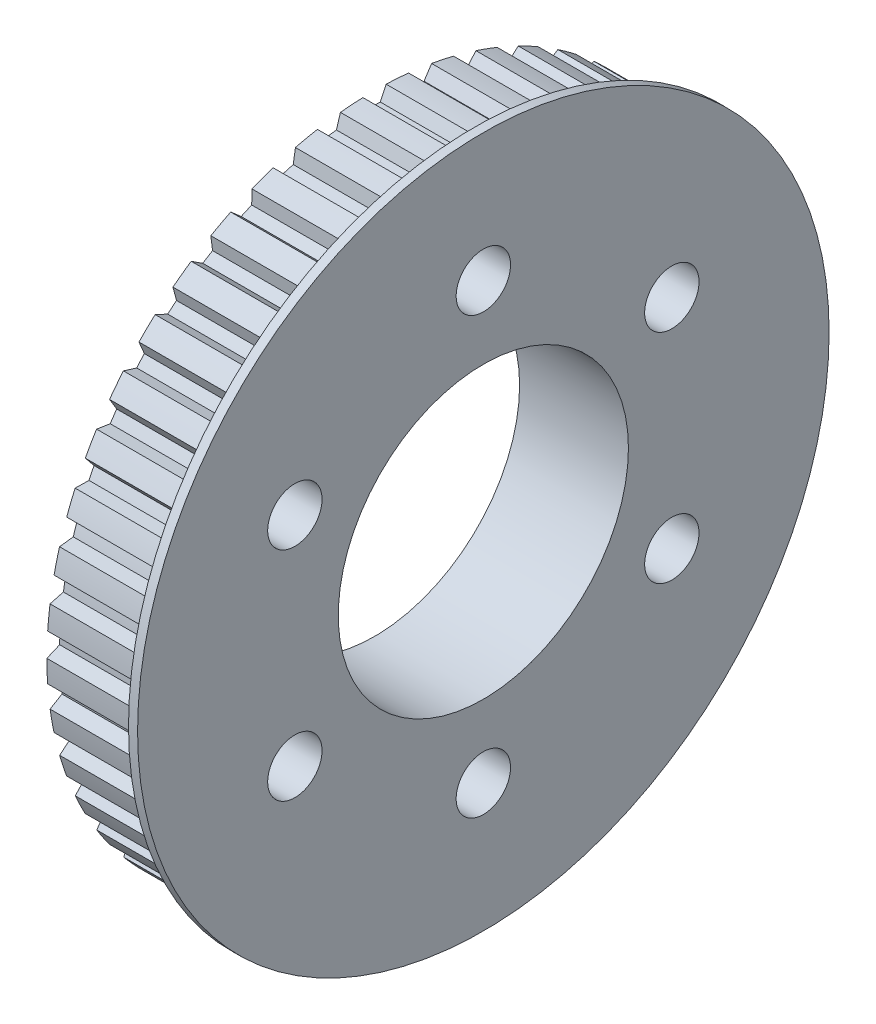
SolidWorks part; units mm, degrees
ref_plane "Front Plane" through (0, 0, 0) normal (0, 0, 1) x (1, 0, 0)
ref_plane "Top Plane" through (0, 0, 0) normal (0, 1, 0) x (1, 0, 0)
ref_plane "Right Plane" through (0, 0, 0) normal (1, 0, 0) x (0, 0, -1)
sketch "Sketch1" plane through (0, 0, 0) normal (1, 0, 0) x (0, 0, -1)
  line L0 (0, 36.13) -> (0, 0) construction
  circle A0 centre (0, 0) radius 36.13
  circle A1 centre (0, 0) radius 16
  point P19 (0, 0)
  dimension "D1" = 72.26
  dimension "D2" = 32
extrude "Boss-Extrude1" add sketch "Sketch1" along normal blind 11
sketch "Sketch2" plane through (0, 0, 0) normal (-1, 0, 0) x (0, 0, 1)
  line L0 (0, 0) -> (0, 36.13) construction
  line L1 (1.2799, 36.1073) -> (0.635, 34.7242)
  line L2 (-1.2799, 36.1073) -> (-0.635, 34.7242)
  line L3 (6.2926, 35.5778) -> (5.4615, 34.2979)
  line L4 (3.7577, 35.9341) -> (4.2039, 34.4746)
  line L5 (11.1829, 34.3558) -> (10.1817, 33.204)
  line L6 (8.7222, 35.0614) -> (8.9609, 33.5541)
  line L7 (15.8554, 32.4651) -> (14.7037, 31.4639)
  line L8 (13.5169, 33.5063) -> (13.5435, 31.9804)
  line L9 (20.2194, 29.9425) -> (18.9395, 29.1113)
  line L10 (18.0485, 31.299) -> (17.8625, 29.7843)
  line L11 (24.1898, 26.8371) -> (22.8067, 26.1921)
  line L12 (22.2289, 28.4825) -> (21.8339, 27.0084)
  line L13 (27.6894, 23.2093) -> (26.23, 22.7632)
  line L14 (25.9765, 25.1117) -> (25.3802, 23.7069)
  line L15 (30.6501, 19.1299) -> (29.1427, 18.8911)
  line L16 (29.2186, 21.2521) -> (28.4326, 19.9439)
  line L17 (33.0141, 14.678) -> (31.4882, 14.6514)
  line L18 (31.892, 16.9788) -> (30.9315, 15.7928)
  line L19 (34.7356, 9.9405) -> (33.2209, 10.1265)
  line L20 (33.9446, 12.3751) -> (32.8285, 11.3343)
  line L21 (35.781, 5.0095) -> (34.3069, 5.4045)
  line L22 (35.3365, 7.5305) -> (34.0864, 6.6551)
  line L23 (36.13, -0.019) -> (34.7252, 0.5773)
  line L24 (36.0407, 2.5393) -> (34.6809, 1.8464)
  line L25 (35.7757, -5.0472) -> (34.4676, -4.2612)
  line L26 (36.0433, -2.5013) -> (34.6003, -2.9982)
  line L27 (34.7251, -9.9771) -> (33.5391, -9.0166)
  line L28 (35.3444, -7.4932) -> (33.8463, -7.7844)
  line L29 (32.9987, -14.7128) -> (31.9579, -13.5966)
  line L30 (33.9576, -12.3393) -> (32.4336, -12.4192)
  line L31 (30.6299, -19.1621) -> (29.7546, -17.912)
  line L32 (31.9098, -16.9452) -> (30.3895, -16.8122)
  line L33 (27.665, -23.2385) -> (26.9721, -21.8787)
  line L34 (29.241, -21.2213) -> (27.754, -20.878)
  line L35 (24.1616, -26.8625) -> (23.6647, -25.4196)
  line L36 (26.003, -25.0843) -> (24.5782, -24.5374)
  line L37 (20.1879, -29.9638) -> (19.8967, -28.4657)
  line L38 (22.2588, -28.4591) -> (20.9241, -27.7192)
  line L39 (15.8213, -32.4818) -> (15.7414, -30.9577)
  line L40 (18.0815, -31.28) -> (16.8627, -30.3615)
  line L41 (11.1467, -34.3675) -> (11.2797, -32.8472)
  line L42 (13.5522, -33.492) -> (12.473, -32.4129)
  line L43 (6.2552, -35.5844) -> (6.5985, -34.0974)
  line L44 (8.7591, -35.0522) -> (7.8407, -33.8334)
  line L45 (1.2419, -36.1086) -> (1.7888, -34.6839)
  line L46 (3.7955, -35.9301) -> (3.0557, -34.5953)
  line L47 (-3.7955, -35.9301) -> (-3.0557, -34.5953)
  line L48 (-1.2419, -36.1086) -> (-1.7888, -34.6839)
  line L49 (-8.7591, -35.0522) -> (-7.8407, -33.8334)
  line L50 (-6.2552, -35.5844) -> (-6.5985, -34.0974)
  line L51 (-13.5522, -33.492) -> (-12.473, -32.4129)
  line L52 (-11.1467, -34.3675) -> (-11.2797, -32.8472)
  line L53 (-18.0815, -31.28) -> (-16.8627, -30.3615)
  line L54 (-15.8213, -32.4818) -> (-15.7414, -30.9577)
  line L55 (-22.2588, -28.4591) -> (-20.9241, -27.7192)
  line L56 (-20.1879, -29.9638) -> (-19.8967, -28.4657)
  line L57 (-26.003, -25.0843) -> (-24.5782, -24.5374)
  line L58 (-24.1616, -26.8625) -> (-23.6647, -25.4196)
  line L59 (-29.241, -21.2213) -> (-27.754, -20.878)
  line L60 (-27.665, -23.2385) -> (-26.9721, -21.8787)
  line L61 (-31.9098, -16.9452) -> (-30.3895, -16.8122)
  line L62 (-30.6299, -19.1621) -> (-29.7546, -17.912)
  line L63 (-33.9576, -12.3393) -> (-32.4336, -12.4192)
  line L64 (-32.9987, -14.7128) -> (-31.9579, -13.5966)
  line L65 (-35.3444, -7.4932) -> (-33.8463, -7.7844)
  line L66 (-34.7251, -9.9771) -> (-33.5391, -9.0166)
  line L67 (-36.0433, -2.5013) -> (-34.6003, -2.9982)
  line L68 (-35.7757, -5.0472) -> (-34.4676, -4.2612)
  line L69 (-36.0407, 2.5393) -> (-34.6809, 1.8464)
  line L70 (-36.13, -0.019) -> (-34.7252, 0.5773)
  line L71 (-35.3365, 7.5305) -> (-34.0864, 6.6551)
  line L72 (-35.781, 5.0095) -> (-34.3069, 5.4045)
  line L73 (-33.9446, 12.3751) -> (-32.8285, 11.3343)
  line L74 (-34.7356, 9.9405) -> (-33.2209, 10.1265)
  line L75 (-31.892, 16.9788) -> (-30.9315, 15.7928)
  line L76 (-33.0141, 14.678) -> (-31.4882, 14.6514)
  line L77 (-29.2186, 21.2521) -> (-28.4326, 19.9439)
  line L78 (-30.6501, 19.1299) -> (-29.1427, 18.8911)
  line L79 (-25.9765, 25.1117) -> (-25.3802, 23.7069)
  line L80 (-27.6894, 23.2093) -> (-26.23, 22.7632)
  line L81 (-22.2289, 28.4825) -> (-21.8339, 27.0084)
  line L82 (-24.1898, 26.8371) -> (-22.8067, 26.1921)
  line L83 (-18.0485, 31.299) -> (-17.8625, 29.7843)
  line L84 (-20.2194, 29.9425) -> (-18.9395, 29.1113)
  line L85 (-13.5169, 33.5063) -> (-13.5435, 31.9804)
  line L86 (-15.8554, 32.4651) -> (-14.7037, 31.4639)
  line L87 (-8.7222, 35.0614) -> (-8.9609, 33.5541)
  line L88 (-11.1829, 34.3558) -> (-10.1817, 33.204)
  line L89 (-3.7577, 35.9341) -> (-4.2039, 34.4746)
  line L90 (-6.2926, 35.5778) -> (-5.4615, 34.2979)
  circle A0 centre (0, 0) radius 36.13 construction
  arc A1 (1.2799, 36.1073) -> (-1.2799, 36.1073) centre (0, 0) ccw
  arc A2 (0.635, 34.7242) -> (-0.635, 34.7242) centre (0, 0) ccw
  arc A3 (6.2926, 35.5778) -> (3.7577, 35.9341) centre (0, 0) ccw
  arc A4 (5.4615, 34.2979) -> (4.2039, 34.4746) centre (0, 0) ccw
  arc A5 (11.1829, 34.3558) -> (8.7222, 35.0614) centre (0, 0) ccw
  arc A6 (10.1817, 33.204) -> (8.9609, 33.5541) centre (0, 0) ccw
  arc A7 (15.8554, 32.4651) -> (13.5169, 33.5063) centre (0, 0) ccw
  arc A8 (14.7037, 31.4639) -> (13.5435, 31.9804) centre (0, 0) ccw
  arc A9 (20.2194, 29.9425) -> (18.0485, 31.299) centre (0, 0) ccw
  arc A10 (18.9395, 29.1113) -> (17.8625, 29.7843) centre (0, 0) ccw
  arc A11 (24.1898, 26.8371) -> (22.2289, 28.4825) centre (0, 0) ccw
  arc A12 (22.8067, 26.1921) -> (21.8339, 27.0084) centre (0, 0) ccw
  arc A13 (27.6894, 23.2093) -> (25.9765, 25.1117) centre (0, 0) ccw
  arc A14 (26.23, 22.7632) -> (25.3802, 23.7069) centre (0, 0) ccw
  arc A15 (30.6501, 19.1299) -> (29.2186, 21.2521) centre (0, 0) ccw
  arc A16 (29.1427, 18.8911) -> (28.4326, 19.9439) centre (0, 0) ccw
  arc A17 (33.0141, 14.678) -> (31.892, 16.9788) centre (0, 0) ccw
  arc A18 (31.4882, 14.6514) -> (30.9315, 15.7928) centre (0, 0) ccw
  arc A19 (34.7356, 9.9405) -> (33.9446, 12.3751) centre (0, 0) ccw
  arc A20 (33.2209, 10.1265) -> (32.8285, 11.3343) centre (0, 0) ccw
  arc A21 (35.781, 5.0095) -> (35.3365, 7.5305) centre (0, 0) ccw
  arc A22 (34.3069, 5.4045) -> (34.0864, 6.6551) centre (0, 0) ccw
  arc A23 (36.13, -0.019) -> (36.0407, 2.5393) centre (0, 0) ccw
  arc A24 (34.7252, 0.5773) -> (34.6809, 1.8464) centre (0, 0) ccw
  arc A25 (35.7757, -5.0472) -> (36.0433, -2.5013) centre (0, 0) ccw
  arc A26 (34.4676, -4.2612) -> (34.6003, -2.9982) centre (0, 0) ccw
  arc A27 (34.7251, -9.9771) -> (35.3444, -7.4932) centre (0, 0) ccw
  arc A28 (33.5391, -9.0166) -> (33.8463, -7.7844) centre (0, 0) ccw
  arc A29 (32.9987, -14.7128) -> (33.9576, -12.3393) centre (0, 0) ccw
  arc A30 (31.9579, -13.5966) -> (32.4336, -12.4192) centre (0, 0) ccw
  arc A31 (30.6299, -19.1621) -> (31.9098, -16.9452) centre (0, 0) ccw
  arc A32 (29.7546, -17.912) -> (30.3895, -16.8122) centre (0, 0) ccw
  arc A33 (27.665, -23.2385) -> (29.241, -21.2213) centre (0, 0) ccw
  arc A34 (26.9721, -21.8787) -> (27.754, -20.878) centre (0, 0) ccw
  arc A35 (24.1616, -26.8625) -> (26.003, -25.0843) centre (0, 0) ccw
  arc A36 (23.6647, -25.4196) -> (24.5782, -24.5374) centre (0, 0) ccw
  arc A37 (20.1879, -29.9638) -> (22.2588, -28.4591) centre (0, 0) ccw
  arc A38 (19.8967, -28.4657) -> (20.9241, -27.7192) centre (0, 0) ccw
  arc A39 (15.8213, -32.4818) -> (18.0815, -31.28) centre (0, 0) ccw
  arc A40 (15.7414, -30.9577) -> (16.8627, -30.3615) centre (0, 0) ccw
  arc A41 (11.1467, -34.3675) -> (13.5522, -33.492) centre (0, 0) ccw
  arc A42 (11.2797, -32.8472) -> (12.473, -32.4129) centre (0, 0) ccw
  arc A43 (6.2552, -35.5844) -> (8.7591, -35.0522) centre (0, 0) ccw
  arc A44 (6.5985, -34.0974) -> (7.8407, -33.8334) centre (0, 0) ccw
  arc A45 (1.2419, -36.1086) -> (3.7955, -35.9301) centre (0, 0) ccw
  arc A46 (1.7888, -34.6839) -> (3.0557, -34.5953) centre (0, 0) ccw
  arc A47 (-3.7955, -35.9301) -> (-1.2419, -36.1086) centre (0, 0) ccw
  arc A48 (-3.0557, -34.5953) -> (-1.7888, -34.6839) centre (0, 0) ccw
  arc A49 (-8.7591, -35.0522) -> (-6.2552, -35.5844) centre (0, 0) ccw
  arc A50 (-7.8407, -33.8334) -> (-6.5985, -34.0974) centre (0, 0) ccw
  arc A51 (-13.5522, -33.492) -> (-11.1467, -34.3675) centre (0, 0) ccw
  arc A52 (-12.473, -32.4129) -> (-11.2797, -32.8472) centre (0, 0) ccw
  arc A53 (-18.0815, -31.28) -> (-15.8213, -32.4818) centre (0, 0) ccw
  arc A54 (-16.8627, -30.3615) -> (-15.7414, -30.9577) centre (0, 0) ccw
  arc A55 (-22.2588, -28.4591) -> (-20.1879, -29.9638) centre (0, 0) ccw
  arc A56 (-20.9241, -27.7192) -> (-19.8967, -28.4657) centre (0, 0) ccw
  arc A57 (-26.003, -25.0843) -> (-24.1616, -26.8625) centre (0, 0) ccw
  arc A58 (-24.5782, -24.5374) -> (-23.6647, -25.4196) centre (0, 0) ccw
  arc A59 (-29.241, -21.2213) -> (-27.665, -23.2385) centre (0, 0) ccw
  arc A60 (-27.754, -20.878) -> (-26.9721, -21.8787) centre (0, 0) ccw
  arc A61 (-31.9098, -16.9452) -> (-30.6299, -19.1621) centre (0, 0) ccw
  arc A62 (-30.3895, -16.8122) -> (-29.7546, -17.912) centre (0, 0) ccw
  arc A63 (-33.9576, -12.3393) -> (-32.9987, -14.7128) centre (0, 0) ccw
  arc A64 (-32.4336, -12.4192) -> (-31.9579, -13.5966) centre (0, 0) ccw
  arc A65 (-35.3444, -7.4932) -> (-34.7251, -9.9771) centre (0, 0) ccw
  arc A66 (-33.8463, -7.7844) -> (-33.5391, -9.0166) centre (0, 0) ccw
  arc A67 (-36.0433, -2.5013) -> (-35.7757, -5.0472) centre (0, 0) ccw
  arc A68 (-34.6003, -2.9982) -> (-34.4676, -4.2612) centre (0, 0) ccw
  arc A69 (-36.0407, 2.5393) -> (-36.13, -0.019) centre (0, 0) ccw
  arc A70 (-34.6809, 1.8464) -> (-34.7252, 0.5773) centre (0, 0) ccw
  arc A71 (-35.3365, 7.5305) -> (-35.781, 5.0095) centre (0, 0) ccw
  arc A72 (-34.0864, 6.6551) -> (-34.3069, 5.4045) centre (0, 0) ccw
  arc A73 (-33.9446, 12.3751) -> (-34.7356, 9.9405) centre (0, 0) ccw
  arc A74 (-32.8285, 11.3343) -> (-33.2209, 10.1265) centre (0, 0) ccw
  arc A75 (-31.892, 16.9788) -> (-33.0141, 14.678) centre (0, 0) ccw
  arc A76 (-30.9315, 15.7928) -> (-31.4882, 14.6514) centre (0, 0) ccw
  arc A77 (-29.2186, 21.2521) -> (-30.6501, 19.1299) centre (0, 0) ccw
  arc A78 (-28.4326, 19.9439) -> (-29.1427, 18.8911) centre (0, 0) ccw
  arc A79 (-25.9765, 25.1117) -> (-27.6894, 23.2093) centre (0, 0) ccw
  arc A80 (-25.3802, 23.7069) -> (-26.23, 22.7632) centre (0, 0) ccw
  arc A81 (-22.2289, 28.4825) -> (-24.1898, 26.8371) centre (0, 0) ccw
  arc A82 (-21.8339, 27.0084) -> (-22.8067, 26.1921) centre (0, 0) ccw
  arc A83 (-18.0485, 31.299) -> (-20.2194, 29.9425) centre (0, 0) ccw
  arc A84 (-17.8625, 29.7843) -> (-18.9395, 29.1113) centre (0, 0) ccw
  arc A85 (-13.5169, 33.5063) -> (-15.8554, 32.4651) centre (0, 0) ccw
  arc A86 (-13.5435, 31.9804) -> (-14.7037, 31.4639) centre (0, 0) ccw
  arc A87 (-8.7222, 35.0614) -> (-11.1829, 34.3558) centre (0, 0) ccw
  arc A88 (-8.9609, 33.5541) -> (-10.1817, 33.204) centre (0, 0) ccw
  arc A89 (-3.7577, 35.9341) -> (-6.2926, 35.5778) centre (0, 0) ccw
  arc A90 (-4.2039, 34.4746) -> (-5.4615, 34.2979) centre (0, 0) ccw
  point P10 (0, 34.73)
  point P18 (4.8335, 34.392)
  point P23 (9.5729, 33.3846)
  point P28 (14.126, 31.7274)
  point P33 (18.4041, 29.4527)
  point P38 (22.324, 26.6047)
  point P43 (25.8094, 23.2389)
  point P48 (28.7925, 19.4208)
  point P53 (31.2151, 15.2246)
  point P58 (33.0302, 10.7322)
  point P63 (34.2024, 6.0308)
  point P68 (34.7088, 1.2121)
  point P73 (34.5397, -3.6303)
  point P78 (33.6984, -8.4019)
  point P83 (32.2011, -13.0101)
  point P88 (30.0771, -17.365)
  point P93 (27.3676, -21.3819)
  point P98 (24.1255, -24.9827)
  point P103 (20.4138, -28.0972)
  point P108 (16.3047, -30.6648)
  point P113 (11.8784, -32.6355)
  point P118 (7.2208, -33.9711)
  point P123 (2.4226, -34.6454)
  point P128 (-2.4226, -34.6454)
  point P133 (-7.2208, -33.9711)
  point P138 (-11.8784, -32.6355)
  point P143 (-16.3047, -30.6648)
  point P148 (-20.4138, -28.0972)
  point P153 (-24.1255, -24.9827)
  point P158 (-27.3676, -21.3819)
  point P159 (0, 0)
  point P161 (-30.0771, -17.365)
  point P166 (-32.2011, -13.0101)
  point P171 (-33.6984, -8.4019)
  point P176 (-34.5397, -3.6303)
  point P181 (-34.7088, 1.2121)
  point P186 (-34.2024, 6.0308)
  point P191 (-33.0302, 10.7322)
  point P196 (-31.2151, 15.2246)
  point P201 (-28.7925, 19.4208)
  point P206 (-25.8094, 23.2389)
  point P211 (-22.324, 26.6047)
  point P216 (-18.4041, 29.4527)
  point P221 (-14.126, 31.7274)
  point P226 (-9.5729, 33.3846)
  point P231 (-4.8335, 34.392)
  dimension "D1" = 1.4
  dimension "D2" = 25
  dimension "D3" = 0.635
  dimension "D4" = 45
extrude "Cut-Extrude1" cut sketch "Sketch2" against normal through all
sketch "Sketch4" plane through (11, 0, 0) normal (1, 0, 0) x (0, 0, -1)
  circle A0 centre (0, 0) radius 38.13
  circle A1 centre (0, 0) radius 16 construction
  circle A2 centre (0, 0) radius 16
  arc A3 (3.7577, 35.9341) -> (1.2799, 36.1073) centre (0, 0) ccw construction
  dimension "D1" = 2
extrude "Boss-Extrude2" add sketch "Sketch4" along normal blind 1
sketch "Sketch5" plane through (0, 0, 0) normal (-1, 0, 0) x (0, 0, 1)
  line L0 (0, 0) -> (0, -24) construction
  circle A0 centre (0, -24) radius 3
  circle A1 centre (-20.7846, -12) radius 3
  circle A2 centre (-20.7846, 12) radius 3
  circle A3 centre (0, 24) radius 3
  circle A4 centre (20.7846, 12) radius 3
  circle A5 centre (20.7846, -12) radius 3
  point P16 (0, 0)
  dimension "D1" = 6
  dimension "D2" = 24
  dimension "D3" = 6
extrude "Cut-Extrude2" cut sketch "Sketch5" against normal through all
